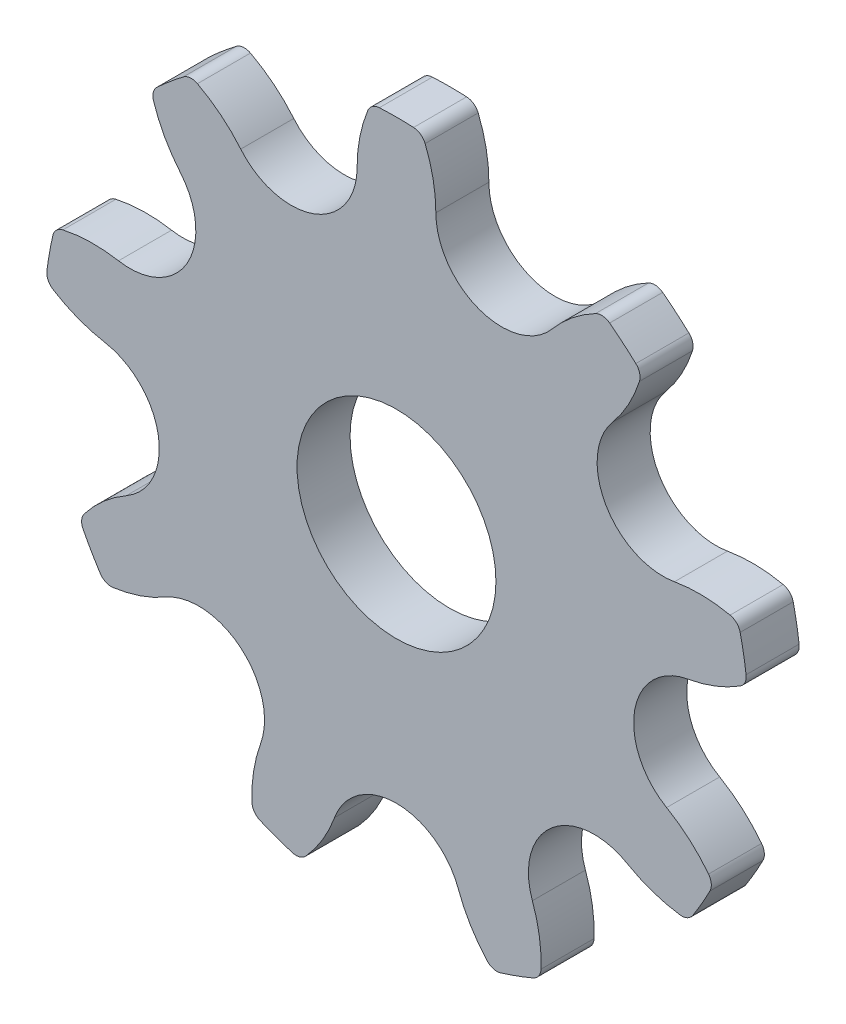
SolidWorks part; units mm, degrees
material "AISI 1020 Steel, Cold Rolled"
ref_plane "Front Plane" through (0, 0, 0) normal (0, 0, 1) x (1, 0, 0)
ref_plane "Top Plane" through (0, 0, 0) normal (0, 1, 0) x (1, 0, 0)
ref_plane "Right Plane" through (0, 0, 0) normal (1, 0, 0) x (0, 0, -1)
sketch "Sketch1" plane through (0, 0, 0) normal (0, 0, 1) x (1, 0, 0)
  arc A0 (2.3749, 17.4465) -> (1.7287, 20.7417) centre (-6.35, 17.4465) ccw
  arc A1 (1.7287, 20.7417) -> (1.0323, 21.2347) centre (0.9937, 20.4419) ccw
  arc A2 (1.0323, 21.2347) -> (-1.0323, 21.2347) centre (0, 0) ccw
  arc A3 (-1.0323, 21.2347) -> (-1.7287, 20.7417) centre (-0.9937, 20.4419) ccw
  arc A4 (-1.7287, 20.7417) -> (-2.3749, 17.4465) centre (6.35, 17.4465) ccw
  arc A5 (-2.3749, 17.4465) -> (-9.3951, 14.8913) centre (-6.35, 17.4465) cw
  arc A6 (-9.3951, 14.8913) -> (-12.0082, 17.0002) centre (-16.0788, 9.2831) ccw
  arc A7 (-12.0082, 17.0002) -> (-12.8586, 16.9303) centre (-12.3786, 16.2982) ccw
  arc A8 (-12.8586, 16.9303) -> (-14.4402, 15.6032) centre (0, 0) ccw
  arc A9 (-14.4402, 15.6032) -> (-14.6568, 14.7779) centre (-13.9011, 15.0206) ccw
  arc A10 (-14.6568, 14.7779) -> (-13.0337, 11.8382) centre (-6.35, 17.4465) ccw
  arc A11 (-13.0337, 11.8382) -> (-16.769, 5.3684) centre (-16.0788, 9.2831) cw
  arc A12 (-16.769, 5.3684) -> (-20.1264, 5.3042) centre (-18.2841, -3.224) ccw
  arc A13 (-20.1264, 5.3042) -> (-20.7329, 4.704) centre (-19.9588, 4.5283) ccw
  arc A14 (-20.7329, 4.704) -> (-21.0914, 2.6708) centre (0, 0) ccw
  arc A15 (-21.0914, 2.6708) -> (-20.7268, 1.8993) centre (-20.3039, 2.5711) ccw
  arc A16 (-20.7268, 1.8993) -> (-17.5938, 0.6907) centre (-16.0788, 9.2831) ccw
  arc A17 (-17.5938, 0.6907) -> (-16.2965, -6.6665) centre (-18.2841, -3.224) cw
  arc A18 (-16.2965, -6.6665) -> (-18.8272, -8.8737) centre (-11.9341, -14.2225) ccw
  arc A19 (-18.8272, -8.8737) -> (-18.906, -9.7234) centre (-18.2001, -9.3603) ccw
  arc A20 (-18.906, -9.7234) -> (-17.8737, -11.5113) centre (0, 0) ccw
  arc A21 (-17.8737, -11.5113) -> (-17.0985, -11.8679) centre (-17.2063, -11.0816) ccw
  arc A22 (-17.0985, -11.8679) -> (-13.9216, -10.78) centre (-18.2841, -3.224) ccw
  arc A23 (-13.9216, -10.78) -> (-8.1987, -15.5821) centre (-11.9341, -14.2225) cw
  arc A24 (-8.1987, -15.5821) -> (-8.7185, -18.8996) centre (0, -18.5662) ccw
  arc A25 (-8.7185, -18.8996) -> (-8.2327, -19.6011) centre (-7.9254, -18.8692) ccw
  arc A26 (-8.2327, -19.6011) -> (-6.2927, -20.3072) centre (0, 0) ccw
  arc A27 (-6.2927, -20.3072) -> (-5.4696, -20.0821) centre (-6.0577, -19.549) ccw
  arc A28 (-5.4696, -20.0821) -> (-3.7354, -17.2066) centre (-11.9341, -14.2225) ccw
  arc A29 (-3.7354, -17.2066) -> (3.7354, -17.2066) centre (0, -18.5662) cw
  arc A30 (3.7354, -17.2066) -> (5.4696, -20.0821) centre (11.9341, -14.2225) ccw
  arc A31 (5.4696, -20.0821) -> (6.2927, -20.3072) centre (6.0577, -19.549) ccw
  arc A32 (6.2927, -20.3072) -> (8.2327, -19.6011) centre (0, 0) ccw
  arc A33 (8.2327, -19.6011) -> (8.7185, -18.8996) centre (7.9254, -18.8692) ccw
  arc A34 (8.7185, -18.8996) -> (8.1987, -15.5821) centre (0, -18.5662) ccw
  arc A35 (8.1987, -15.5821) -> (13.9216, -10.78) centre (11.9341, -14.2225) cw
  arc A36 (13.9216, -10.78) -> (17.0985, -11.8679) centre (18.2841, -3.224) ccw
  arc A37 (17.0985, -11.8679) -> (17.8737, -11.5113) centre (17.2063, -11.0816) ccw
  arc A38 (17.8737, -11.5113) -> (18.906, -9.7234) centre (0, 0) ccw
  arc A39 (18.906, -9.7234) -> (18.8272, -8.8737) centre (18.2001, -9.3603) ccw
  arc A40 (18.8272, -8.8737) -> (16.2965, -6.6665) centre (11.9341, -14.2225) ccw
  arc A41 (16.2965, -6.6665) -> (17.5938, 0.6907) centre (18.2841, -3.224) cw
  arc A42 (17.5938, 0.6907) -> (20.7268, 1.8993) centre (16.0788, 9.2831) ccw
  arc A43 (20.7268, 1.8993) -> (21.0914, 2.6708) centre (20.3039, 2.5711) ccw
  arc A44 (21.0914, 2.6708) -> (20.7329, 4.704) centre (0, 0) ccw
  arc A45 (20.7329, 4.704) -> (20.1264, 5.3042) centre (19.9588, 4.5283) ccw
  arc A46 (20.1264, 5.3042) -> (16.769, 5.3684) centre (18.2841, -3.224) ccw
  arc A47 (16.769, 5.3684) -> (13.0337, 11.8382) centre (16.0788, 9.2831) cw
  arc A48 (13.0337, 11.8382) -> (14.6568, 14.7779) centre (6.35, 17.4465) ccw
  arc A49 (14.6568, 14.7779) -> (14.4402, 15.6032) centre (13.9011, 15.0206) ccw
  arc A50 (14.4402, 15.6032) -> (12.8586, 16.9303) centre (0, 0) ccw
  arc A51 (12.8586, 16.9303) -> (12.0082, 17.0002) centre (12.3786, 16.2982) ccw
  arc A52 (12.0082, 17.0002) -> (9.3951, 14.8913) centre (16.0788, 9.2831) ccw
  arc A53 (9.3951, 14.8913) -> (2.3749, 17.4465) centre (6.35, 17.4465) cw
extrude "Boss-Extrude1" add sketch "Sketch1" against normal blind 3.2
sketch "Sketch2" plane through (0, 0, 0) normal (0, 0, 1) x (1, 0, 0)
  circle A0 centre (0, 0) radius 6
extrude "Cut-Extrude1" cut sketch "Sketch2" against normal blind 10
ref_plane "Plane1" through (0, 0, -1.6) normal (0, 0, 1) x (1, 0, 0)
sketch "Sketch3" plane through (0, 0, -1.6) normal (0, 0, 1) x (1, 0, 0)
  circle A0 centre (0, 0) radius 21.2598 construction
